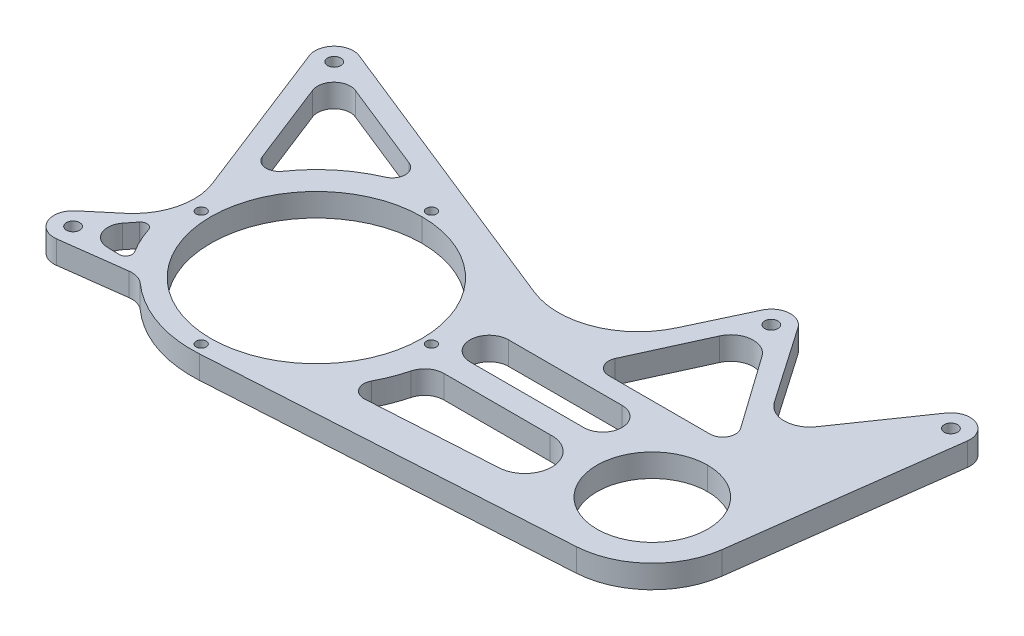
SolidWorks part; units mm, degrees
material "7075-T6 (SN)"
ref_plane "X-Y Datum" through (0, 0, 0) normal (0, 0, 1) x (1, 0, 0)
ref_plane "X-Z Datum" through (0, 0, 0) normal (0, 1, 0) x (1, 0, 0)
ref_plane "Y-Z Datum" through (0, 0, 0) normal (1, 0, 0) x (0, 0, -1)
sketch "Sketch1" plane through (0, 0, 0) normal (0, 1, 0) x (1, 0, 0)
  line L0 (-228.6, -165.1) -> (-123.19, -116.0015) construction
  line L1 (0, 0) -> (54.61, -127) construction
  line L2 (-123.19, -116.0015) -> (54.61, -127) construction
  line L3 (-228.6, -165.1) -> (-228.6, 0) construction
  line L4 (-116.84, 0) -> (0, 0) construction
  line L5 (-228.6, 0) -> (-116.84, 0) construction
  line L10 (-228.6, 0) -> (-123.19, -116.0015) construction
  line L11 (-123.19, -116.0015) -> (10.0337, -23.3342) construction
  line L15 (-207.9749, -9.9568) -> (-62.7807, -68.145)
  line L17 (17.8716, -17.9218) -> (44.1595, -55.9906)
  line L18 (1.4126, -19.2843) -> (-12.1766, -48.2122)
  line L20 (-211.7072, -147.0868) -> (-198.1514, -135.6819)
  line L21 (-220.3888, -22.2676) -> (-189.4301, -101.4224)
  line L22 (-172.4434, -159.7008) -> (-204.3552, -163.8219)
  line L23 (54.61, -249.6025) -> (54.61, -4.3975) construction
  line L24 (109.22, 0) -> (54.61, -127) construction
  line L26 (91.3484, -17.9218) -> (65.0605, -55.9906)
  line L27 (108.6299, -24.5765) -> (94.4666, -132.2431)
  line L28 (-119.4523, -177.801) -> (57.0369, -167.1267)
  circle A0 centre (-211.5182, -18.7982) radius 9.525 construction
  circle A2 centre (10.0337, -23.3342) radius 9.525 construction
  circle A3 centre (-211.5182, -18.7982) radius 3.3 construction
  circle A4 centre (-205.5752, -154.3754) radius 3.3 construction
  circle A5 centre (-123.19, -116.0015) radius 52.3875
  circle A6 centre (54.61, -127) radius 27.5
  circle A7 centre (0, 0) radius 12.7 construction
  circle A8 centre (-228.6, -165.1) radius 12.7 construction
  circle A9 centre (-228.6, 0) radius 12.7 construction
  circle A10 centre (10.0337, -23.3342) radius 3.3 construction
  circle A11 centre (-123.19, -173.1515) radius 2.5 construction
  circle A14 centre (-123.19, -116.0015) radius 61.9125 construction
  circle A15 centre (-123.19, -116.0015) radius 57.15 construction
  circle A17 centre (-205.5752, -154.3754) radius 9.525 construction
  circle A18 centre (54.61, -127) radius 31.75 construction
  circle A19 centre (-48.0406, -31.3647) radius 39.624 construction
  arc A20 (-12.1766, -48.2122) -> (-62.7807, -68.145) centre (-48.0406, -31.3647) cw
  arc A25 (1.4126, -19.2843) -> (17.8716, -17.9218) centre (10.0337, -23.3342) cw
  circle A27 centre (-217.6792, -112.471) radius 30.3329 construction
  arc A29 (-198.1514, -135.6819) -> (-189.4301, -101.4224) centre (-217.6792, -112.471) ccw
  arc A30 (-220.3888, -22.2676) -> (-207.9749, -9.9568) centre (-211.5182, -18.7982) cw
  arc A31 (-164.4265, -162.1827) -> (-119.4523, -177.801) centre (-123.19, -116.0015) ccw
  circle A32 centre (-171.1504, -169.7128) radius 10.0952 construction
  arc A33 (-204.3552, -163.8219) -> (-211.7072, -147.0868) centre (-205.5752, -154.3754) cw
  arc A34 (-172.4434, -159.7008) -> (-164.4265, -162.1827) centre (-171.1504, -169.7128) cw
  circle A35 centre (109.22, 0) radius 12.7 construction
  circle A36 centre (99.1863, -23.3342) radius 3.3 construction
  circle A37 centre (99.1863, -23.3342) radius 9.525 construction
  arc A38 (91.3484, -17.9218) -> (108.5063, -25.2997) centre (99.1863, -23.3342) cw
  arc A39 (44.1595, -55.9906) -> (65.0605, -55.9906) centre (54.61, -48.7741) ccw
  arc A40 (54.61, -167.2) -> (94.4666, -132.2431) centre (54.61, -127) ccw
  circle A42 centre (54.61, -127) radius 40.2 construction
  point P36 (-123.19, -116.0015)
  point P57 (54.61, -127)
  point P68 (54.61, -71.1243)
  point P71 (101.16, -127)
  dimension "D1" = 165.1
  dimension "D2" = 105.41
  dimension "D8" = 25.4
  dimension "D9" = 104.775
  dimension "D10" = 55
  dimension "D11" = 19.05
  dimension "D12" = 6.6
  dimension "D23" = 5
  dimension "D14" = 123.825
  dimension "D19" = 79.248
  dimension "D20" = 31.3647
  dimension "D16" = 63.5
  dimension "D25" = 20.1904
  dimension "D21" = 20.9
  dimension "D26" = 60.6657
  dimension "D28" = 12.7
  dimension "D3" = 111.76
  dimension "D4" = 228.6
  dimension "D5" = 127
  dimension "D6" = 49.0985
  dimension "D7" = 283.21
  dimension "D13" = 25.4
  dimension "D15" = 25.4
  dimension "D17" = 25.4
  dimension "D18" = 48.0406
  dimension "D22" = 34.4248
  dimension "D24" = 57.15
  dimension "D27" = 10.9208
  dimension "D29" = 109.22
  dimension "D30" = 12.7
extrude "Boss-Extrude1" add sketch "Sketch1" along normal mid plane 11.43
hole_wizard "M6 Clearance Hole1" positions "Sketch8" profile "Sketch9" hole size "M6" standard "ANSI Metric" end condition through all
sketch "Sketch8" plane through (0, -5.715, 0) normal (0, -1, 0) x (-1, 0, 0)
  point P0 (-222.0845, -125.8217)
  point P2 (-10.0337, -23.3342)
  point P5 (-99.1863, -23.3342)
  point P8 (211.5182, -18.7982)
  point P11 (205.5752, -154.3754)
sketch "Sketch9" plane through (222.0845, -5.715, 125.8217) normal (1, 0, 0) x (0, 0, -1)
  line L0 (0, 0) -> (0, 11.43)
  line L1 (0, 11.43) -> (3.3, 11.43)
  line L2 (3.3, 11.43) -> (3.3, 0)
  line L5 (3.3, 0) -> (0, 0)
  line L11 (0, -6.35) -> (0, 107.95) construction
  dimension "Thru Hole Dia." = 6.6
  dimension "Thru Hole Depth" = 11.43
hole_wizard "Ø5.0mm Dowel Hole1" positions "Sketch10" profile "Sketch11" hole size "Ø5.0" standard "ANSI Metric" end condition through all
sketch "Sketch10" plane through (0, 5.715, 0) normal (0, 1, 0) x (1, 0, 0)
  point P0 (-123.19, -173.1515)
sketch "Sketch11" plane through (-123.19, 5.715, 173.1515) normal (1, 0, 0) x (0, 0, 1)
  line L0 (0, 0) -> (0, 11.43)
  line L1 (0, 11.43) -> (2.5, 11.43)
  line L2 (2.5, 11.43) -> (2.5, 0)
  line L5 (2.5, 0) -> (0, 0)
  line L11 (0, -6.35) -> (0, 107.95) construction
  dimension "Thru Hole Dia." = 5
  dimension "Thru Hole Depth" = 11.43
ref_point "Point1"
ref_point "Point2"
ref_plane "Plane1" through (-123.19, 0, 0) normal (1, 0, 0) x (0, 0, -1)
ref_plane "Plane2" through (54.61, 0, 0) normal (1, 0, 0) x (0, 0, -1)
split line "Split Line1"
split line "Split Line2"
pattern_circular "CirPattern1" count 4 over 360 about axis through (-123.19, 0, 116.0015) along (0, 1, 0) of "Ø5.0mm Dowel Hole1"
sketch "Sketch12" plane through (0, -5.715, 0) normal (0, -1, 0) x (1, 0, 0)
  line L0 (-14.2347, 76.5807) -> (2.0163, 40.925)
  line L1 (21.2013, 39.1139) -> (46.9848, 75.5459)
  line L2 (-204.6607, 36.3314) -> (-188.6269, 77.3262)
  line L3 (-194.0427, 25.8017) -> (-149.3861, 43.6983)
  line L5 (-8.4565, 85.5642) -> (41.8016, 85.5642)
  line L17 (-190.9857, 136.0276) -> (-194.6927, 140.6895)
  line L18 (-182.1426, 155.013) -> (-188.0965, 154.851)
  circle A1 centre (10.0337, 23.3342) radius 3.3 construction
  circle A3 centre (-8.4565, 79.2142) radius 6.35 construction
  circle A4 centre (41.8016, 79.2142) radius 6.35 construction
  circle A5 centre (12.1294, 45.5343) radius 11.114 construction
  arc A6 (2.0163, 40.925) -> (21.2013, 39.1139) centre (12.1294, 45.5343) ccw
  arc A8 (46.9848, 75.5459) -> (41.8016, 85.5642) centre (41.8016, 79.2142) ccw
  arc A9 (-14.2347, 76.5807) -> (-8.4565, 85.5642) centre (-8.4565, 79.2142) cw
  circle A10 centre (-182.5949, 74.967) radius 6.477 construction
  circle A11 centre (-151.7955, 49.7105) radius 6.477 construction
  circle A14 centre (-197.0734, 33.3639) radius 8.1469 construction
  arc A15 (-204.6607, 36.3314) -> (-194.0427, 25.8017) centre (-197.0734, 33.3639) ccw
  arc A25 (-149.3861, 43.6983) -> (-149.2293, 55.6575) centre (-151.7955, 49.7105) ccw
  circle A27 centre (-123.19, 116.0015) radius 65.7225 construction
  arc A28 (-149.2293, 55.6575) -> (-177.2657, 78.6482) centre (-123.19, 116.0015) cw
  arc A29 (-188.6269, 77.3262) -> (-177.2657, 78.6482) centre (-182.5949, 74.967) cw
  circle A31 centre (-182.0558, 151.8264) radius 3.1877 construction
  circle A32 centre (-188.4906, 138.0115) radius 3.1877 construction
  circle A33 centre (-187.859, 146.1234) radius 8.7308 construction
  arc A34 (-185.4699, 136.9934) -> (-179.3328, 150.1692) centre (-123.19, 116.0015) cw
  arc A35 (-179.3328, 150.1692) -> (-182.1426, 155.013) centre (-182.0558, 151.8264) ccw
  arc A36 (-185.4699, 136.9934) -> (-190.9857, 136.0276) centre (-188.4906, 138.0115) cw
  arc A37 (-194.6927, 140.6895) -> (-188.0965, 154.851) centre (-187.859, 146.1234) cw
  dimension "D3" = 12.7
  dimension "D4" = 22.2001
  dimension "D5" = 12.954
  dimension "D9" = 6.3754
  dimension "D6" = 55.88
extrude "Cut-Extrude3" cut sketch "Sketch12" against normal through all
sketch "Sketch13" plane through (0, -5.715, 0) normal (0, -1, 0) x (1, 0, 0)
  line L0 (-48.7514, 114.0965) -> (7.6366, 114.0965)
  line L1 (-48.7514, 95.0465) -> (7.6366, 95.0465)
  line L6 (-50.3282, 125.5265) -> (2.4477, 125.5265)
  line L9 (-59.3095, 156.2605) -> (4.0747, 152.4269)
  line L10 (-119.4523, 177.801) -> (57.0369, 167.1267) construction
  line L11 (2.4477, 125.5265) -> (4.0747, 152.4269) construction
  circle A0 centre (-48.7514, 104.5715) radius 9.525 construction
  circle A3 centre (7.6366, 104.5715) radius 9.525 construction
  arc A4 (-48.7514, 95.0465) -> (-48.7514, 114.0965) centre (-48.7514, 104.5715) cw
  arc A5 (7.6366, 95.0465) -> (7.6366, 114.0965) centre (7.6366, 104.5715) ccw
  circle A12 centre (-50.3282, 135.0515) radius 9.525 construction
  circle A14 centre (-59.3095, 149.7835) radius 6.477 construction
  arc A15 (-59.5434, 132.6421) -> (-65.0352, 146.7556) centre (-123.19, 116.0015) ccw
  arc A16 (-65.0352, 146.7556) -> (-58.2001, 156.1648) centre (-59.3095, 149.7835) cw
  arc A17 (-59.5434, 132.6421) -> (-50.3282, 125.5265) centre (-50.3282, 135.0515) ccw
  arc A21 (4.0747, 152.4269) -> (2.4477, 125.5265) centre (3.2612, 138.9767) cw
  circle A29 centre (-123.19, 116.0015) radius 65.786 construction
  dimension "D1" = 19.05
  dimension "D2" = 131.572
  dimension "D5" = 12.954
  dimension "D8" = 63.5
  dimension "D3" = 11.43
  dimension "D4" = 56.388
  dimension "D7" = 14.732
  dimension "D6" = 33.782
extrude "Cut-Extrude4" cut sketch "Sketch13" against normal through all
